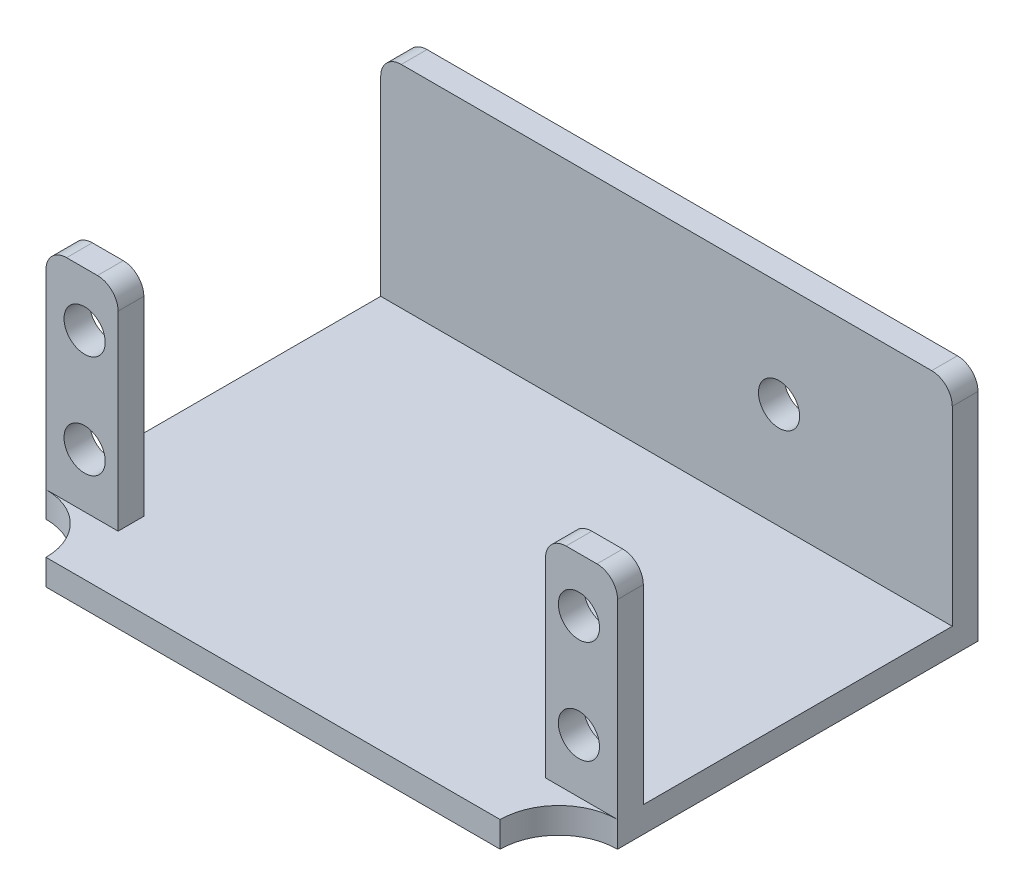
SolidWorks part; units mm, degrees
ref_plane "Front" through (0, 0, 0) normal (0, 0, 1) x (1, 0, 0)
ref_plane "Top" through (0, 0, 0) normal (0, 1, 0) x (1, 0, 0)
ref_plane "Right" through (0, 0, 0) normal (1, 0, 0) x (0, 0, -1)
sketch "Sketch1" plane through (0, 0, 0) normal (0, 1, 0) x (1, 0, 0)
  line L1 (0, 0) -> (55.5, 0)
  line L2 (0, 0) -> (0, 38.2)
  line L3 (0, 38.2) -> (55.5, 38.2)
  line L4 (55.5, 0) -> (55.5, 38.2)
  dimension "D1" = 38.2
  dimension "D2" = 55.5
extrude "bracketBase" add sketch "Sketch1" along normal blind 2.5
ref_plane "referencePlane1" through (0, 0, -8.2) normal (0, 0, 1) x (1, 0, 0)
sketch "Sketch2" plane through (0, 0, -8.2) normal (0, 0, 1) x (1, 0, 0)
  line L0 (27.75, 2.5) -> (27.75, 23) construction
  line L1 (0, 2.5) -> (7, 2.5)
  line L2 (0, 2.5) -> (0, 23)
  line L3 (0, 23) -> (7, 23)
  line L4 (7, 2.5) -> (7, 23)
  line L5 (0, 2.5) -> (55.5, 2.5) construction
  line L6 (55.5, 23) -> (48.5, 23)
  line L7 (48.5, 2.5) -> (48.5, 23)
  line L8 (55.5, 2.5) -> (48.5, 2.5)
  line L9 (55.5, 2.5) -> (55.5, 23)
  dimension "D1" = 20.5
  dimension "D2" = 7
extrude "servoMountingHoleTabs" add sketch "Sketch2" along normal blind 2.5
sketch "Sketch3" plane through (0, 0, -5.7) normal (0, 0, 1) x (1, 0, 0)
  line L0 (0, 12.75) -> (7, 12.75) construction
  line L3 (0, 23) -> (0, 2.5) construction
  line L4 (7, 2.5) -> (7, 23) construction
  line L5 (7, 23) -> (0, 23) construction
  line L6 (27.75, 2.5) -> (27.75, 23) construction
  line L7 (0, 2.5) -> (55.5, 2.5) construction
  circle A0 centre (3.75, 17.75) radius 2
  circle A1 centre (3.75, 7.75) radius 2
  circle A2 centre (51.75, 7.75) radius 2
  circle A3 centre (51.75, 17.75) radius 2
  dimension "D1" = 4
  dimension "D2" = 3.75
  dimension "D3" = 5.25
extrude "servoMountingHoles" cut sketch "Sketch3" against normal blind 2.5
sketch "Sketch4" plane through (0, 0, 0) normal (0, 1, 0) x (1, 0, 0)
  line L0 (55.5, 8.2) -> (55.5, 38.2) construction
  line L1 (0, 38.2) -> (55.5, 38.2)
  line L2 (0, 38.2) -> (0, 40.7)
  line L3 (0, 40.7) -> (55.5, 40.7)
  line L4 (55.5, 38.2) -> (55.5, 40.7)
  dimension "D1" = 2.5
extrude "baseWall" add sketch "Sketch4" along normal up to surface (23 mm away) up to face at (3.5, 23, -6.95)
sketch "Sketch6" plane through (0, 2.5, 0) normal (0, 1, 0) x (1, 0, 0)
  circle A0 centre (0, 0) radius 5.7
  circle A1 centre (55.5, 0) radius 5.7
extrude "baseTrim" cut sketch "Sketch6" against normal blind 2.5
fillet "Fillet1" radius 2 6 edges at (7, 23, -6.95) (48.5, 23, -6.95) (0, 23, -6.95) (55.5, 23, -6.95) (55.5, 23, -39.45) (0, 23, -39.45)
sketch "Sketch7" plane through (0, 0, -40.7) normal (0, 0, -1) x (-1, 0, 0)
  line L0 (0, 21) -> (0, 0) construction
  line L1 (-55.5, 0) -> (0, 0) construction
  circle A0 centre (-16.819, 12.75) radius 2
  dimension "D1" = 4
  dimension "D2" = 16.819
  dimension "D3" = 12.75
extrude "M4mountingHole" cut sketch "Sketch7" against normal blind 10
sketch "Sketch8" plane through (0, 0, -40.7) normal (0, 0, -1) x (-1, 0, 0)
  line L0 (-27.75, 23) -> (-27.75, 0) construction
  line L1 (-2, 23) -> (-53.5, 23) construction
  line L2 (-55.5, 0) -> (0, 0) construction
  circle A0 centre (-16.819, 12.75) radius 2 construction
  circle A1 centre (-16.819, 12.75) radius 2 construction
  circle A2 centre (-38.681, 12.75) radius 2
extrude "Cut-Extrude1" cut sketch "Sketch8" against normal blind 10
sketch "Sketch9" plane through (0, 0, -40.7) normal (0, 0, -1) x (-1, 0, 0)
  circle A0 centre (-16.819, 12.75) radius 2 construction
  circle A1 centre (-16.819, 12.75) radius 2
extrude "Boss-Extrude1" add sketch "Sketch9" against normal up to surface (2.5 mm away) up to face at (36.681, 12.75, -38.2)
